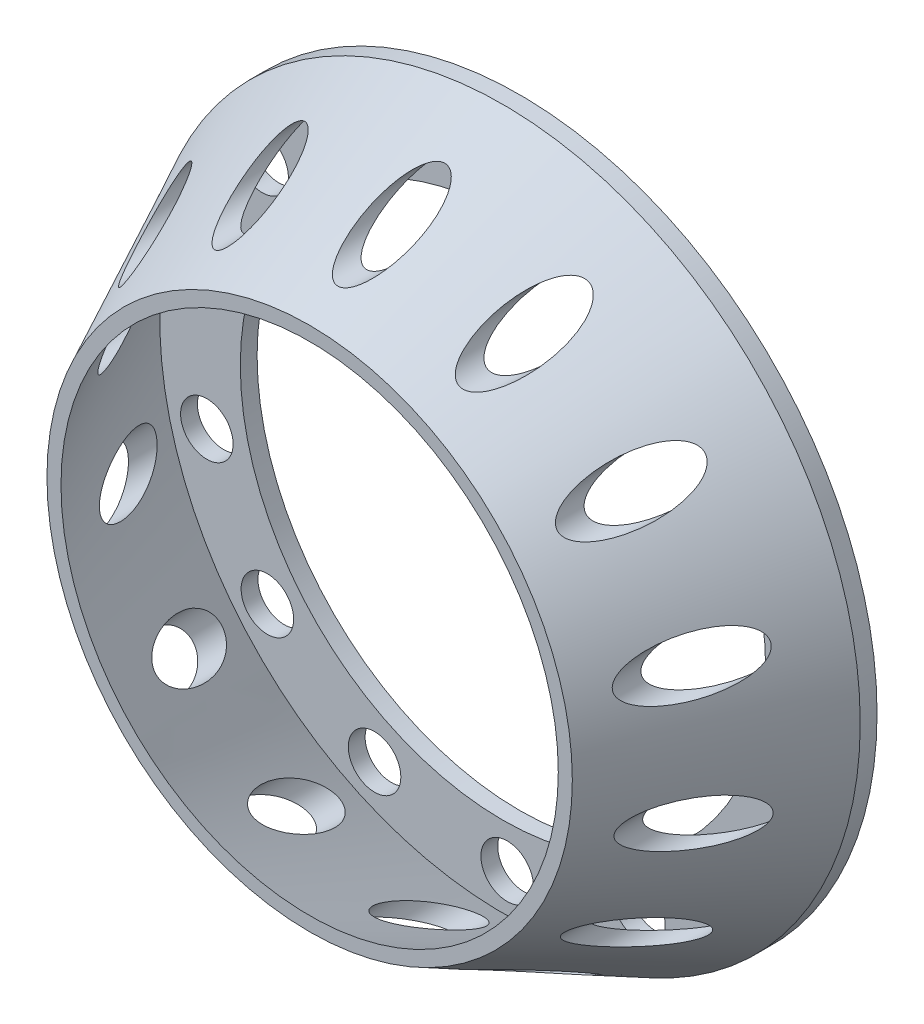
SolidWorks part; units mm, degrees
ref_plane "Front Plane" through (0, 0, 0) normal (0, 0, 1) x (1, 0, 0)
ref_plane "Top Plane" through (0, 0, 0) normal (0, 1, 0) x (1, 0, 0)
ref_plane "Right Plane" through (0, 0, 0) normal (1, 0, 0) x (0, 0, -1)
sketch "Sketch1" plane through (0, 0, 0) normal (0, 0, 1) x (1, 0, 0)
  circle A0 centre (0, 0) radius 34
  dimension "D1" = 68
ref_plane "Plane1" through (0, 0, 18.4) normal (0, 0, 1) x (1, 0, 0)
sketch "Sketch2" plane through (0, 0, 18.4) normal (0, 0, 1) x (1, 0, 0)
  circle A0 centre (0, 0) radius 25
  point P0 (0, 0)
  dimension "D1" = 50
loft "Loft1" add profiles "Sketch1", "Sketch2"
shell "Shell1" thickness 1.2
sketch "Sketch3" plane through (0, 0, 0) normal (0, 0, 1) x (1, 0, 0)
  circle A0 centre (0, 0) radius 34 construction
  circle A1 centre (0, 0) radius 34
  circle A2 centre (0, 0) radius 25
  dimension "D1" = 9
extrude "Boss-Extrude1" add sketch "Sketch3" against normal blind 1.6
sketch "Sketch4" plane through (0, 0, 18.4) normal (0, 0, 1) x (1, 0, 0)
  circle A0 centre (-22.9201, 17.7671) radius 2.5
  circle A1 centre (-12.9414, 25.9523) radius 2.5
  circle A2 centre (-0.3995, 28.9972) radius 2.5
  circle A3 centre (12.2215, 26.299) radius 2.5
  circle A4 centre (22.4219, 18.3918) radius 2.5
  circle A5 centre (28.1813, 6.842) radius 2.5
  circle A6 centre (28.3591, -6.063) radius 2.5
  circle A7 centre (22.9201, -17.7671) radius 2.5
  circle A8 centre (12.9414, -25.9523) radius 2.5
  circle A9 centre (0.3995, -28.9972) radius 2.5
  circle A10 centre (-12.2215, -26.299) radius 2.5
  circle A11 centre (-22.4219, -18.3918) radius 2.5
  circle A12 centre (-28.1813, -6.842) radius 2.5
  circle A13 centre (-28.3591, 6.063) radius 2.5
  point P2 (0, 0)
  point P33 (0, 0)
  dimension "D2" = 5
  dimension "D1" = 29
  dimension "D3" = 14
extrude "Cut-Extrude1" cut sketch "Sketch4" against normal through all
